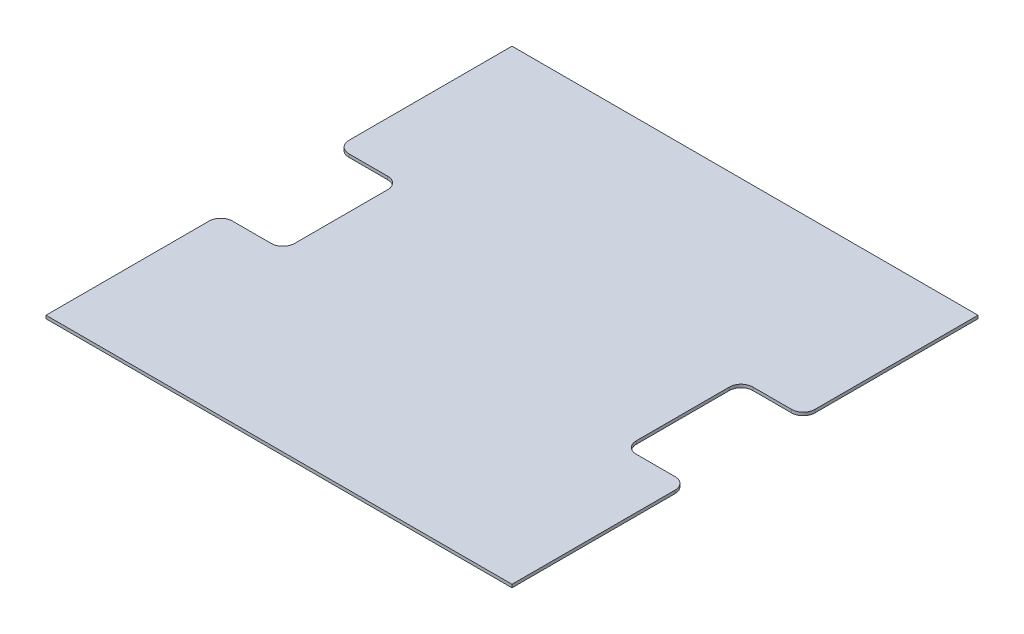
SolidWorks part; units mm, degrees
ref_plane "前视基准面" through (0, 0, 0) normal (0, 0, 1) x (1, 0, 0)
ref_plane "上视基准面" through (0, 0, 0) normal (0, 1, 0) x (1, 0, 0)
ref_plane "右视基准面" through (0, 0, 0) normal (1, 0, 0) x (0, 0, -1)
sketch "草图1" plane through (0, 0, 0) normal (0, 1, 0) x (1, 0, 0)
  line L4 (-300, -300) -> (300, -300)
  line L5 (-300, -300) -> (-300, 300)
  line L6 (-300, 300) -> (300, 300)
  line L7 (300, -300) -> (300, 300)
  line L8 (-300, -300) -> (300, 300) construction
  line L9 (-300, 300) -> (300, -300) construction
  point P0 (0, 0)
  dimension "D1" = 600
  dimension "D2" = 600
extrude "凸台-拉伸1" add sketch "草图1" along normal blind 4
sketch "草图2" plane through (0, 0, 0) normal (0, -1, 0) x (1, 0, 0)
  line L0 (0, 0) -> (406.9589, 0) construction
  line L1 (300, 300) -> (300, -300) construction
  line L2 (300, 75) -> (220, 75)
  line L3 (300, 75) -> (300, -75)
  line L4 (300, -75) -> (220, -75)
  line L5 (220, 75) -> (220, -75)
  point P9 (220, 0)
  dimension "D1" = 80
  dimension "D2" = 150
extrude "切除-拉伸1" cut sketch "草图2" against normal up to surface (4 mm away) up to face at (0, 4, 0)
mirror "镜向1" about plane through (0, 0, 0) normal (1, 0, 0) of "切除-拉伸1"
fillet "圆角1" radius 15 8 edges at (220, 2, -75) (300, 2, -75) (300, 2, 75) (220, 2, 75) (-300, 2, 75) (-220, 2, 75) (-220, 2, -75) (-300, 2, -75)
